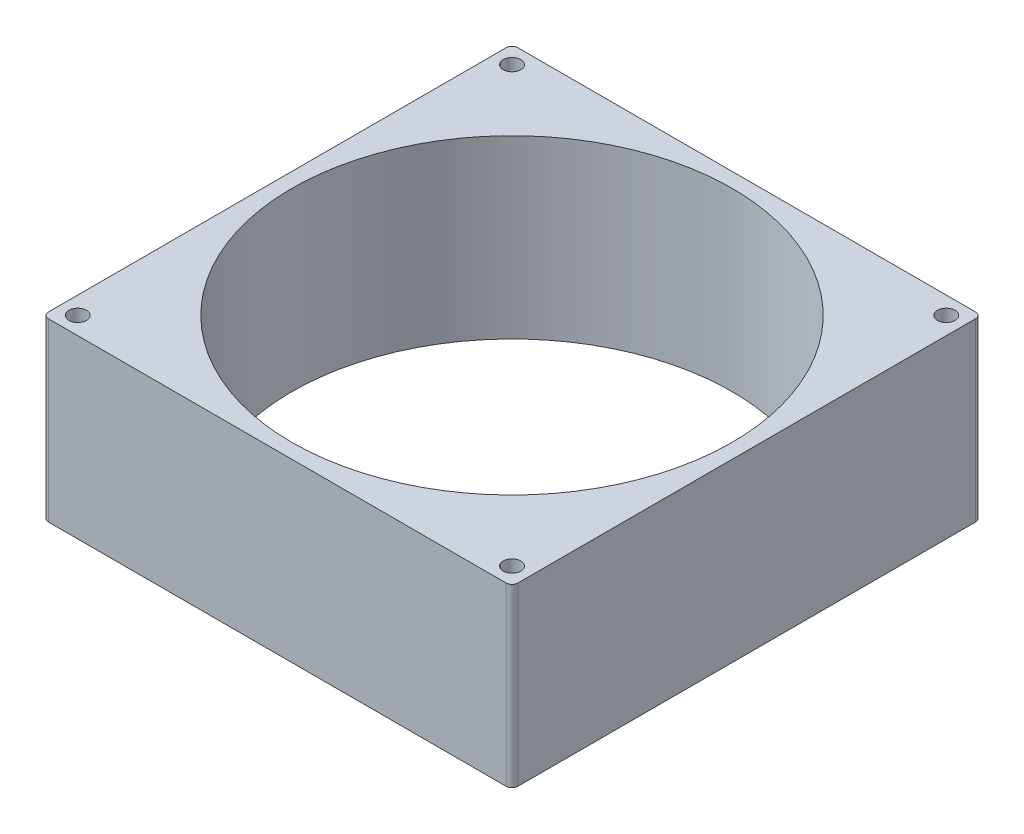
SolidWorks part; units mm, degrees
material "ABS PC"
ref_plane "Front Plane" through (0, 0, 0) normal (0, 0, 1) x (1, 0, 0)
ref_plane "Top Plane" through (0, 0, 0) normal (0, 1, 0) x (1, 0, 0)
ref_plane "Right Plane" through (0, 0, 0) normal (1, 0, 0) x (0, 0, -1)
sketch "Sketch1" plane through (0, 0, 0) normal (0, 1, 0) x (1, 0, 0)
  line L1 (-40, 40) -> (40, 40)
  line L2 (-40, 40) -> (-40, -40)
  line L3 (-40, -40) -> (40, -40)
  line L4 (40, 40) -> (40, -40)
  line L5 (-40, 40) -> (40, -40) construction
  line L6 (-40, -40) -> (40, 40) construction
  circle A0 centre (0, 0) radius 37.5
  circle A1 centre (-37, 37) radius 1.5
  circle A2 centre (37, 37) radius 1.5
  circle A3 centre (37, -37) radius 1.5
  circle A4 centre (-37, -37) radius 1.5
  point P0 (0, 0)
  dimension "D2" = 75
  dimension "D3" = 3
  dimension "D4" = 3
  dimension "D1" = 80
extrude "Boss-Extrude1" add sketch "Sketch1" along normal blind 30
fillet "Fillet1" radius 1 4 edges at (-40, 15, 40) (-40, 15, -40) (40, 15, -40) (40, 15, 40)
